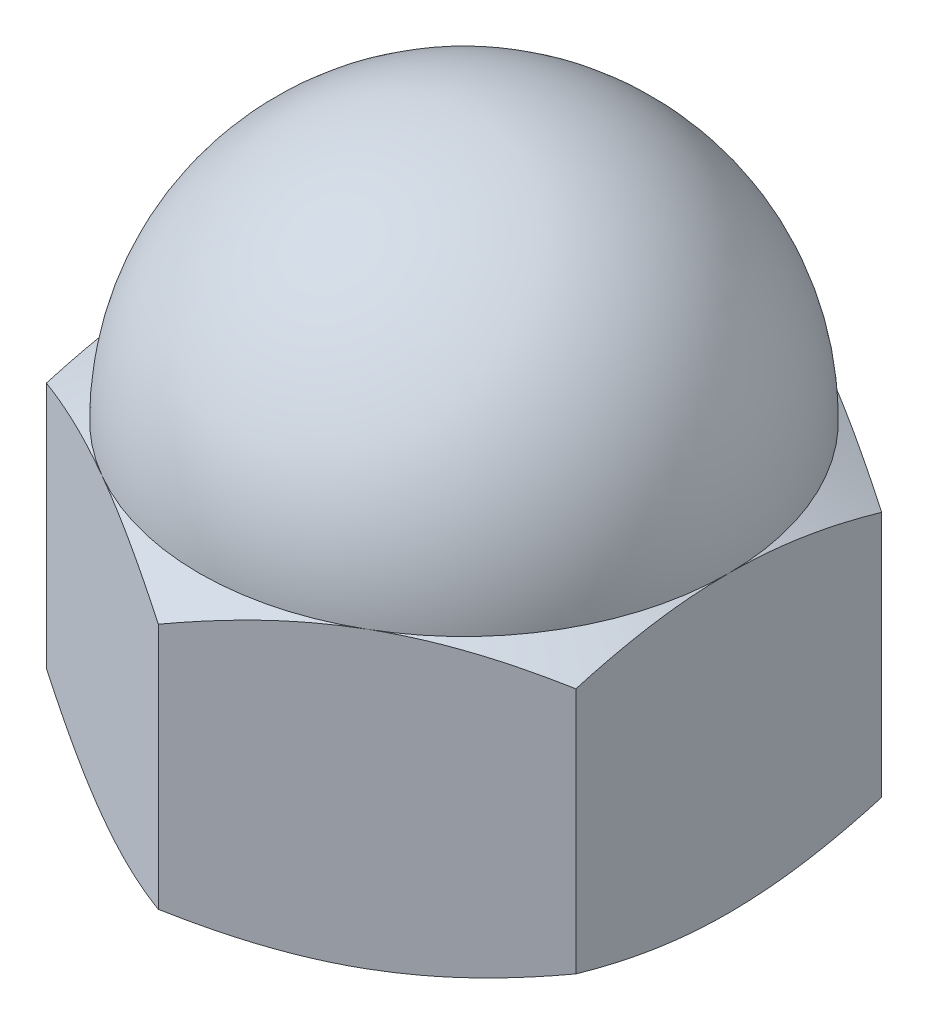
SolidWorks part; units mm, degrees
ref_plane "前视基准面" through (0, 0, 0) normal (0, 0, 1) x (1, 0, 0)
ref_plane "上视基准面" through (0, 0, 0) normal (0, 1, 0) x (1, 0, 0)
ref_plane "右视基准面" through (0, 0, 0) normal (1, 0, 0) x (0, 0, -1)
other "Configuration Table"
sketch "草图1" plane through (0, 0, 0) normal (0, 1, 0) x (1, 0, 0)
  line L1 (9, -5.1962) -> (9, 5.1962)
  line L2 (9, 5.1962) -> (0, 10.3923)
  line L3 (0, 10.3923) -> (-9, 5.1962)
  line L4 (-9, 5.1962) -> (-9, -5.1962)
  line L5 (-9, -5.1962) -> (0, -10.3923)
  line L6 (0, -10.3923) -> (9, -5.1962)
  circle A0 centre (0, 0) radius 9 construction
  dimension "D1" = 18
extrude "凸台-拉伸1" add sketch "草图1" along normal blind 10
sketch "草图3" plane through (0, 0, 0) normal (1, 0, 0) x (0, 0, -1)
  line L0 (9, 10) -> (10.3923, 9.1962)
  line L1 (5.1962, 10) -> (10.3923, 10) construction
  line L2 (10.3923, 9.1962) -> (10.3923, 10)
  line L3 (10.3923, 10) -> (9, 10)
  line L4 (0, 12.4084) -> (0, -3.8133) construction
  dimension "D1" = 18
  dimension "D2" = 30
revolve "切除-旋转1" cut sketch "草图3" angle 360 about L4
ref_plane "基准面1" through (0, 5, 0) normal (0, 1, 0) x (1, 0, 0)
mirror "镜向1" about plane through (0, 5, 0) normal (0, 1, 0) of "切除-旋转1"
hole_wizard "M12 螺纹孔1" positions "草图6" profile "草图8" tap size "M12" standard "GB" end condition up to next
sketch "草图6" plane through (0, 0, 0) normal (0, -1, 0) x (-1, 0, 0)
  point P0 (0, 0)
sketch "草图8" plane through (0, 0, 0) normal (1, 0, 0) x (0, 0, -1)
  line L0 (0, 0) -> (0, 10)
  line L1 (0, 10) -> (5.1, 10)
  line L2 (5.1, 10) -> (5.1, 0)
  line L5 (5.1, 0) -> (0, 0)
  line L11 (0, -6.35) -> (0, 107.95) construction
  dimension "通孔螺纹孔钻头直径" = 10.2
  dimension "通孔螺纹孔钻头深度" = 10
cosmetic thread "孔螺蚊线2" parameters "D2"=12
chamfer "倒角2" distance 1 angle 45 2 edges at (0, 0, -5.1) (0, 10, 5.1)
sketch "草图9" plane through (0, 0, 0) normal (1, 0, 0) x (0, 0, -1)
  line L0 (0, 21.4793) -> (0, -2.3266) construction
  arc A0 (0, 19) -> (9, 10) centre (0, 10) cw
  dimension "D1" = 9
revolve "旋转-薄壁1" add sketch "草图9" angle 360 about L0
